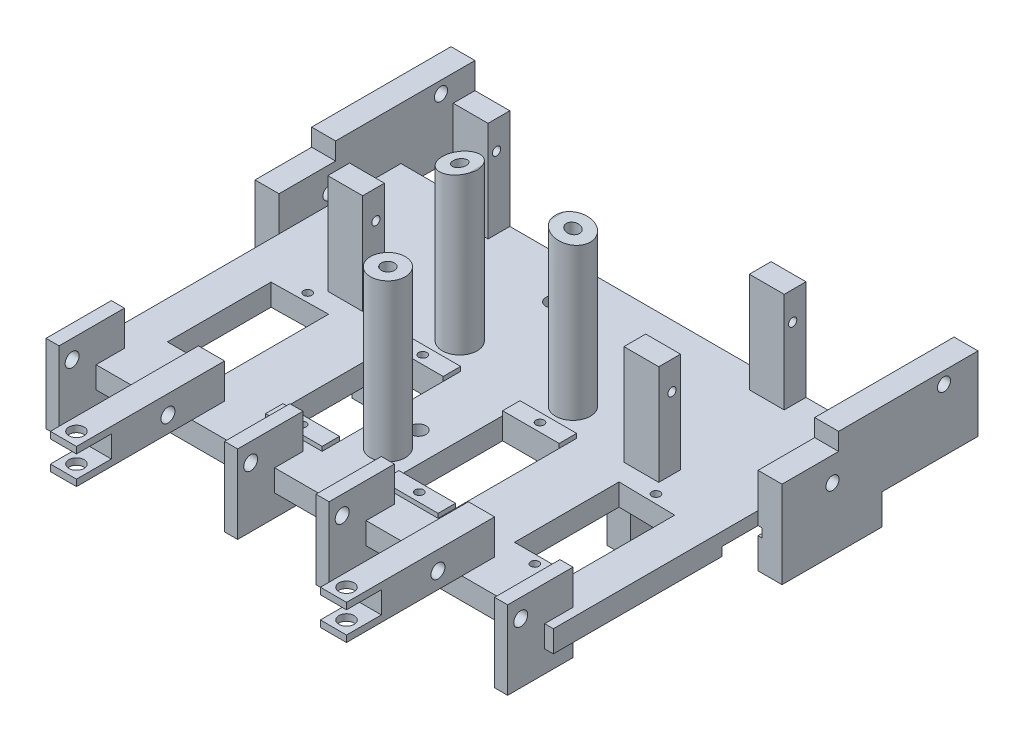
SolidWorks part; units mm, degrees
material "PMMA"
ref_plane "前视基准面" through (0, 0, 0) normal (0, 0, 1) x (1, 0, 0)
ref_plane "上视基准面" through (0, 0, 0) normal (0, 1, 0) x (1, 0, 0)
ref_plane "右视基准面" through (0, 0, 0) normal (1, 0, 0) x (0, 0, -1)
sketch "草图1" plane through (0, 0, 0) normal (0, 1, 0) x (1, 0, 0)
  line L1 (-55, 37.5) -> (55, 37.5)
  line L2 (-55, 37.5) -> (-55, -37.5)
  line L3 (-55, -37.5) -> (55, -37.5)
  line L4 (55, 37.5) -> (55, -37.5)
  line L5 (-55, 37.5) -> (55, -37.5) construction
  line L6 (-55, -37.5) -> (55, 37.5) construction
  point P0 (0, 0)
  dimension "D1" = 110
  dimension "D2" = 75
extrude "凸台-拉伸1" add sketch "草图1" along normal blind 5
sketch "草图4" plane through (0, 5, 0) normal (0, 1, 0) x (1, 0, 0)
  line L1 (-52.5, 9.5) -> (52.5, 9.5)
  line L2 (-52.5, 9.5) -> (-52.5, 37.5)
  line L3 (-52.5, 37.5) -> (52.5, 37.5)
  line L4 (52.5, 9.5) -> (52.5, 37.5)
  line L5 (-52.5, 9.5) -> (52.5, 37.5) construction
  line L6 (-52.5, 37.5) -> (52.5, 9.5) construction
  line L7 (-55, -37.5) -> (55, -37.5) construction
  point P0 (0, 23.5)
  dimension "D1" = 105
  dimension "D2" = 28
  dimension "D3" = 75
extrude "凸台-拉伸4" add sketch "草图4" against normal blind 5
sketch "草图5" plane through (-55, 0, 0) normal (-1, 0, 0) x (0, 0, 1)
  line L1 (-9.5, 13) -> (-32.5, 13)
  line L2 (-9.5, 13) -> (-9.5, -7)
  line L3 (-9.5, -7) -> (-32.5, -7)
  line L4 (-32.5, 13) -> (-32.5, -7)
  line L6 (-37.5, 5) -> (37.5, 5) construction
  line L7 (-37.5, 5) -> (-37.5, 0) construction
  dimension "D1" = 8
  dimension "D2" = 23
  dimension "D3" = 20
  dimension "D4" = 5
extrude "凸台-拉伸5" add sketch "草图5" along normal blind 5.5
sketch "草图6" plane through (-55, 0, 0) normal (-1, 0, 0) x (0, 0, 1)
  line L0 (-37.5, 5) -> (-32.5, 5) construction
  line L1 (-54.5, 17) -> (-22.5, 17)
  line L2 (-54.5, 17) -> (-54.5, 0)
  line L3 (-54.5, 0) -> (-22.5, 0)
  line L4 (-22.5, 17) -> (-22.5, 0)
  line L7 (-37.5, 5) -> (-37.5, 0) construction
  dimension "D1" = 12
  dimension "D2" = 17
  dimension "D3" = 32
  dimension "D4" = 17
extrude "凸台-拉伸6" add sketch "草图6" along normal blind 5.5
sketch "草图8" plane through (0, 5, 0) normal (0, 1, 0) x (1, 0, 0)
  line L0 (55, 37.5) -> (-55, 37.5) construction
  line L1 (-38, 37.5) -> (-30, 37.5)
  line L2 (-38, 37.5) -> (-38, 32.5)
  line L3 (-38, 32.5) -> (-30, 32.5)
  line L4 (-30, 37.5) -> (-30, 32.5)
  line L6 (-38, 8.7) -> (-30, 8.7)
  line L7 (-38, 8.7) -> (-38, 3.7)
  line L8 (-38, 3.7) -> (-30, 3.7)
  line L9 (-30, 8.7) -> (-30, 3.7)
  dimension "D1" = 23.8
  dimension "D2" = 38
  dimension "D3" = 8
  dimension "D4" = 5
  dimension "D5" = 5
extrude "凸台-拉伸7" add sketch "草图8" along normal blind 23
sketch "草图9" plane through (0, 5, 0) normal (0, 1, 0) x (1, 0, 0)
  line L1 (-12, -31) -> (-9, -31)
  line L2 (-12, -31) -> (-12, -46)
  line L3 (-12, -46) -> (-9, -46)
  line L4 (-9, -31) -> (-9, -46)
  dimension "D1" = 12
  dimension "D2" = 3
  dimension "D3" = 15
  dimension "D4" = 46
extrude "凸台-拉伸8" add sketch "草图9" along normal blind 8 and the other way blind 10
sketch "草图10" plane through (0, 5, 0) normal (0, 1, 0) x (1, 0, 0)
  line L0 (-12, -31) -> (-12, -46) construction
  line L1 (-53, -31) -> (-50, -31)
  line L2 (-53, -31) -> (-53, -46)
  line L3 (-53, -46) -> (-50, -46)
  line L4 (-50, -31) -> (-50, -46)
  line L6 (-9, -31) -> (-12, -31) construction
  line L7 (-12, -46) -> (-9, -46) construction
  dimension "D1" = 38
extrude "凸台-拉伸9" add sketch "草图10" along normal blind 8 and the other way blind 10
sketch "草图11" plane through (0, 5, 0) normal (0, 1, 0) x (1, 0, 0)
  line L1 (-34, -30) -> (-28, -30)
  line L2 (-34, -30) -> (-34, -64)
  line L3 (-34, -64) -> (-28, -64)
  line L4 (-28, -30) -> (-28, -64)
  dimension "D1" = 6
  dimension "D2" = 34
  dimension "D3" = 64
  dimension "D4" = 28
extrude "凸台-拉伸10" add sketch "草图11" along normal blind 8
sketch "草图12" plane through (0, 5, 0) normal (0, 1, 0) x (1, 0, 0)
  circle A0 centre (-13, 9) radius 4
  dimension "D1" = 13
  dimension "D2" = 9
  dimension "D3" = 8
extrude "凸台-拉伸11" add sketch "草图12" along normal blind 36
sketch "草图19" plane through (-38, 0, 0) normal (-1, 0, 0) x (0, 0, 1)
  line L1 (-8.7, 28) -> (-8.7, 5) construction
  line L2 (-8.7, 28) -> (-3.7, 28) construction
  line L3 (-32.5, 28) -> (-32.5, 5) construction
  circle A0 centre (-6.75, 21.5) radius 0.95
  circle A1 centre (-34.45, 21.5) radius 0.95
  dimension "D1" = 6.5
  dimension "D2" = 1.95
  dimension "D3" = 1.9
  dimension "D4" = 27.7
  dimension "D5" = 1.9
  dimension "D6" = 1.95
extrude "切除-拉伸8" cut sketch "草图19" against normal up to next
sketch "草图25" plane through (0, 5, 0) normal (0, 1, 0) x (1, 0, 0)
  circle A0 centre (0, -20.5) radius 4
  circle A1 centre (-13, 9) radius 4 construction
  dimension "D1" = 20.5
extrude "凸台-拉伸14" add sketch "草图25" along normal blind 36
sketch "草图26" plane through (0, 0, 0) normal (0, 0, 1) x (1, 0, 0)
  line L0 (-17, 41) -> (-17, 39.644)
  line L1 (-17, 41) -> (-17, 5) construction
  line L2 (-17, 39.644) -> (-9.31, 41)
  line L3 (-9, 41) -> (-17, 41) construction
  line L4 (-9.31, 41) -> (-17, 41)
  dimension "D1" = 10
  dimension "D2" = 0.31
extrude "切除-拉伸14" cut sketch "草图26" against normal blind 36
sketch "草图28" plane through (0, 0, 64) normal (0, 0, 1) x (1, 0, 0)
  line L0 (-34, 13) -> (-34, 5) construction
  line L1 (-34, 11.5) -> (-28, 11.5)
  line L2 (-34, 11.5) -> (-34, 6.5)
  line L3 (-34, 6.5) -> (-28, 6.5)
  line L4 (-28, 11.5) -> (-28, 6.5)
  line L5 (-28, 13) -> (-28, 5) construction
  line L6 (-34, 13) -> (-28, 13) construction
  dimension "D1" = 1.5
  dimension "D2" = 5
extrude "切除-拉伸16" cut sketch "草图28" against normal blind 8
sketch "草图29" plane through (0, 13, 0) normal (0, 1, 0) x (1, 0, 0)
  line L0 (-34, -64) -> (-28, -64) construction
  circle A0 centre (-31, -61) radius 1.75
  point P5 (-31, -64)
  dimension "D1" = 3
  dimension "D2" = 3.5
extrude "切除-拉伸17" cut sketch "草图29" against normal blind 8
sketch "草图30" plane through (-53, 0, 0) normal (-1, 0, 0) x (0, 0, 1)
  line L0 (31, 5) -> (37.5, 5) construction
  circle A0 centre (43, 8.75) radius 1.6
  dimension "D1" = 43
  dimension "D2" = 3.75
  dimension "D3" = 3.2
extrude "切除-拉伸18" cut sketch "草图30" against normal blind 48
sketch "草图31" plane through (0, 5, 0) normal (0, 1, 0) x (1, 0, 0)
  circle A0 centre (0, -13.5) radius 1.75
  circle A1 centre (-10, 27.5) radius 1.75
  circle A2 centre (10, 27.5) radius 1.75
  dimension "D1" = 20
  dimension "D2" = 10
  dimension "D3" = 27.5
  dimension "D4" = 3.5
  dimension "D5" = 3.5
  dimension "D7" = 3.5
  dimension "D6" = 13.5
extrude "切除-拉伸19" cut sketch "草图31" against normal blind 20
sketch "草图35" plane through (-60.5, 0, 0) normal (-1, 0, 0) x (0, 0, 1)
  circle A0 centre (-46.6906, 14.2639) radius 1.5
  circle A1 centre (-21.0894, 7.4378) radius 1.5
  dimension "D1" = 3
  dimension "D2" = 3
extrude "切除-拉伸23" cut sketch "草图35" against normal blind 15
sketch "草图36" plane through (0, 5, 0) normal (0, 1, 0) x (1, 0, 0)
  line L0 (-13.4508, 4.0639) -> (-13.4508, -27.9765) construction
  line L1 (-19.8158, -0.9819) -> (-6.8158, -0.9819)
  line L2 (-19.8158, -0.9819) -> (-19.8158, -24.7819)
  line L3 (-19.8158, -24.7819) -> (-6.8158, -24.7819)
  line L4 (-6.8158, -0.9819) -> (-6.8158, -24.7819)
  line L5 (-33.3471, -0.7664) -> (-33.3471, -24.7819)
  line L6 (-39.9809, 4.2721) -> (-39.9809, -27.7684) construction
  line L7 (-46.3459, -24.7819) -> (-33.3471, -24.7819)
  line L8 (-46.3453, -0.9819) -> (-46.3459, -24.7819)
  line L9 (-46.3453, -0.9819) -> (-33.3471, -0.7664)
  circle A0 centre (-13.4508, 0.9681) radius 0.95
  circle A1 centre (-13.4508, -26.7319) radius 0.95
  circle A2 centre (-39.9809, -26.7319) radius 0.95
  circle A3 centre (-39.98, 1.0739) radius 0.95
  dimension "D3" = 1.9
  dimension "D4" = 1.9
  dimension "D9" = 1.9
  dimension "D10" = 1.9
  dimension "D1" = 23.8
  dimension "D2" = 13
  dimension "D5" = 1.95
  dimension "D6" = 1.95
  dimension "D7" = 23.8
  dimension "D8" = 13
  dimension "D11" = 1.95
  dimension "D12" = 1.95
extrude "切除-拉伸24" cut sketch "草图36" against normal blind 7
sketch "草图37" plane through (0, 0, 0) normal (0, -1, 0) x (1, 0, 0)
  line L1 (-26.6386, -37.023) -> (-32.6386, -37.023)
  line L2 (-26.6386, -37.023) -> (-26.6386, -32.023)
  line L3 (-26.6386, -32.023) -> (-32.6386, -32.023)
  line L4 (-32.6386, -37.023) -> (-32.6386, -32.023)
  line L5 (-26.6386, -8.223) -> (-31.945, -8.223)
  line L6 (-26.6386, -8.223) -> (-26.6386, -3.223)
  line L7 (-26.6386, -3.223) -> (-31.945, -3.223)
  line L8 (-31.945, -8.223) -> (-31.945, -3.223)
  dimension "D1" = 23.8
  dimension "D2" = 6
  dimension "D3" = 5
  dimension "D4" = 5
extrude "凸台-拉伸15" add sketch "草图37" along normal blind 13
sketch "草图38" plane through (-32.6386, 0, 0) normal (-1, 0, 0) x (0, 0, 1)
  line L0 (-32.023, -13) -> (-32.023, 0) construction
  line L1 (-9.5, 0) -> (37.5, 0) construction
  line L3 (-20.123, 2.1642) -> (-20.123, -15.8009) construction
  circle A0 centre (-33.973, -4.5) radius 0.95
  circle A1 centre (-6.273, -4.5) radius 0.95
  dimension "D1" = 1.9
  dimension "D2" = 1.95
  dimension "D3" = 4.5
  dimension "D4" = 11.9
extrude "切除-拉伸25" cut sketch "草图38" against normal blind 13
sketch "草图43" plane through (0, 0, 0) normal (0, -1, 0) x (1, 0, 0)
  line L0 (55, -37.5) -> (-55, -37.5) construction
  line L1 (-55.945, -1.223) -> (-18.6386, -1.223)
  line L2 (-55.945, -1.223) -> (-55.945, -37.5)
  line L3 (-55.945, -37.5) -> (-18.6386, -37.5)
  line L4 (-18.6386, -1.223) -> (-18.6386, -37.5)
  line L5 (-26.6386, -3.223) -> (-31.945, -3.223) construction
  line L6 (-26.6386, -8.223) -> (-26.6386, -3.223) construction
  line L7 (-26.6386, -3.223) -> (-31.945, -3.223) construction
  line L8 (-31.945, -3.223) -> (-31.945, -8.223) construction
  line L9 (-31.945, -8.223) -> (-26.6386, -8.223) construction
  line L10 (-26.6386, -37.023) -> (-26.6386, -32.023) construction
  line L11 (-26.6386, -32.023) -> (-32.6386, -32.023) construction
  line L12 (-32.6386, -32.023) -> (-32.6386, -37.023) construction
  line L13 (-32.6386, -37.023) -> (-26.6386, -37.023) construction
  line L14 (-26.6386, -8.223) -> (-26.6386, -3.223)
  line L15 (-26.6386, -3.223) -> (-31.945, -3.223)
  line L16 (-31.945, -3.223) -> (-31.945, -8.223)
  line L17 (-31.945, -8.223) -> (-26.6386, -8.223)
  line L18 (-26.6386, -37.023) -> (-26.6386, -32.023)
  line L19 (-26.6386, -32.023) -> (-32.6386, -32.023)
  line L20 (-32.6386, -32.023) -> (-32.6386, -37.023)
  line L21 (-32.6386, -37.023) -> (-26.6386, -37.023)
  dimension "D1" = 2
  dimension "D2" = 8
  dimension "D3" = 24
extrude "切除-拉伸28" cut sketch "草图43" against normal blind 2
sketch "草图41" plane through (0, 5, 0) normal (0, 1, 0) x (1, 0, 0)
  line L0 (-19.8158, -0.9819) -> (-19.8158, -24.7819) construction
  line L1 (-6.8158, -0.9819) -> (-19.8158, -0.9819)
  line L2 (-6.8158, -0.9819) -> (-6.8158, 3.0181)
  line L3 (-6.8158, 3.0181) -> (-19.8158, 3.0181)
  line L4 (-19.8158, -0.9819) -> (-19.8158, 3.0181)
  line L5 (-6.8158, -24.7819) -> (-6.8158, -0.9819) construction
  line L6 (-19.8158, -24.7819) -> (-6.8158, -24.7819)
  line L7 (-19.8158, -24.7819) -> (-19.8158, -28.7819)
  line L8 (-19.8158, -28.7819) -> (-6.8158, -28.7819)
  line L9 (-6.8158, -24.7819) -> (-6.8158, -28.7819)
  circle A0 centre (-13.4508, 0.9681) radius 0.95
  circle A1 centre (-13.4508, -26.7319) radius 0.95
  dimension "D3" = 1.9
  dimension "D4" = 1.9
  dimension "D1" = 4
  dimension "D2" = 4
extrude "凸台-拉伸16" add sketch "草图41" along normal blind 1
sketch "草图39" plane through (0, 5, 0) normal (0, 1, 0) x (1, 0, 0)
  circle A0 centre (-13, 9) radius 1.5
  circle A1 centre (0, -20.5) radius 1.5
  dimension "D1" = 3
  dimension "D2" = 3
extrude "切除-拉伸26" cut sketch "草图39" against normal blind 13 and the other way blind 42
mirror "镜向1" about plane through (0, 0, 0) normal (1, 0, 0) of "凸台-拉伸5", "凸台-拉伸6", "凸台-拉伸7", "凸台-拉伸8", "凸台-拉伸9", "凸台-拉伸10", "凸台-拉伸11", "切除-拉伸8", "切除-拉伸14", "切除-拉伸16", "切除-拉伸17", "切除-拉伸18", "切除-拉伸23", "切除-拉伸24", "凸台-拉伸15", "切除-拉伸25", "切除-拉伸28", "凸台-拉伸16", "切除-拉伸26"
